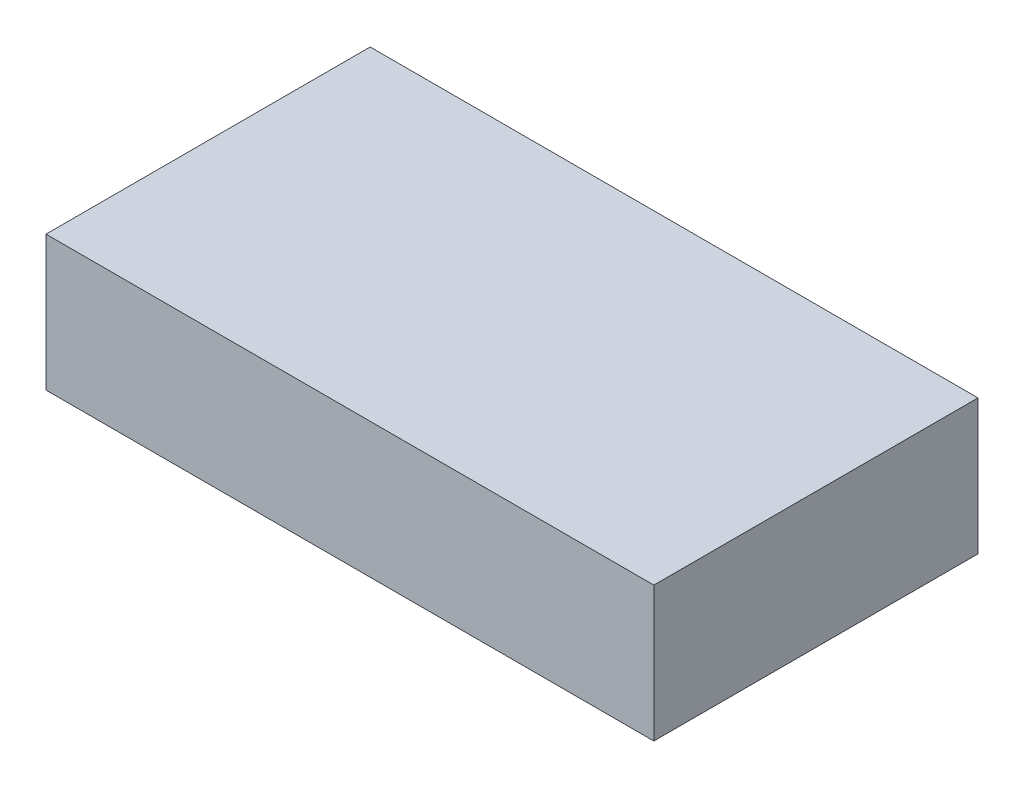
SolidWorks part; units mm, degrees
ref_plane "Front Plane" through (0, 0, 0) normal (0, 0, 1) x (1, 0, 0)
ref_plane "Top Plane" through (0, 0, 0) normal (0, 1, 0) x (1, 0, 0)
ref_plane "Right Plane" through (0, 0, 0) normal (1, 0, 0) x (0, 0, -1)
sketch "Sketch1" plane through (0, 0, 0) normal (0, 1, 0) x (1, 0, 0)
  line L1 (0, 0) -> (45, 0)
  line L2 (0, 0) -> (0, 24)
  line L3 (0, 24) -> (45, 24)
  line L4 (45, 0) -> (45, 24)
  dimension "D1" = 45
  dimension "D2" = 24
extrude "battery model, just a block" add sketch "Sketch1" along normal blind 10
